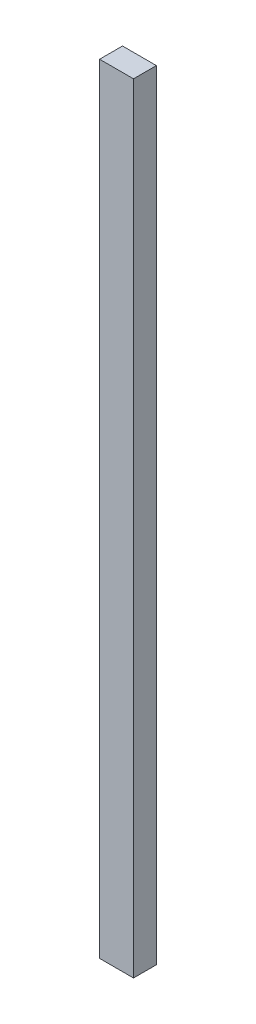
SolidWorks part; units mm, degrees
ref_plane "Front Plane" through (0, 0, 0) normal (0, 0, 1) x (1, 0, 0)
ref_plane "Top Plane" through (0, 0, 0) normal (0, 1, 0) x (1, 0, 0)
ref_plane "Right Plane" through (0, 0, 0) normal (1, 0, 0) x (0, 0, -1)
sketch "Sketch1" plane through (0, 0, 0) normal (0, 1, 0) x (1, 0, 0)
  line L1 (-2.3495, -1.5875) -> (2.3495, -1.5875)
  line L2 (-2.3495, -1.5875) -> (-2.3495, 1.5875)
  line L3 (-2.3495, 1.5875) -> (2.3495, 1.5875)
  line L4 (2.3495, -1.5875) -> (2.3495, 1.5875)
  line L5 (-2.3495, -1.5875) -> (2.3495, 1.5875) construction
  line L6 (-2.3495, 1.5875) -> (2.3495, -1.5875) construction
  point P0 (0, 0)
  dimension "D1" = 3.175
  dimension "D2" = 4.699
extrude "Boss-Extrude1" add sketch "Sketch1" along normal blind 107.95
